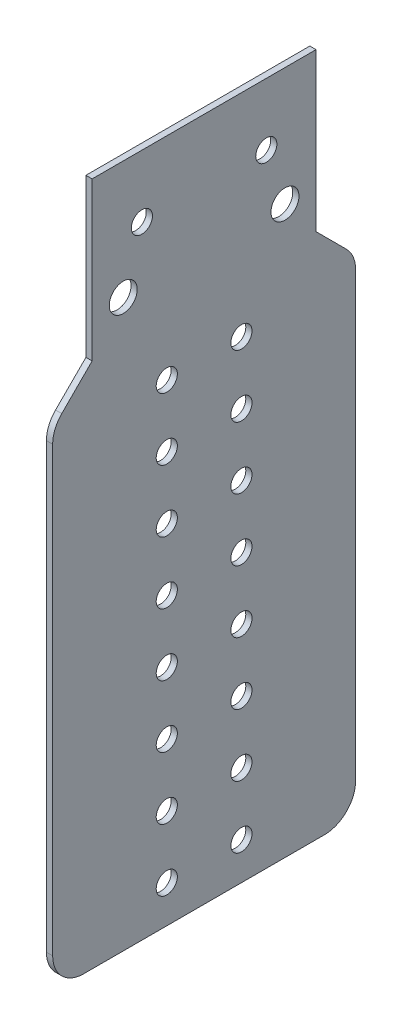
SolidWorks part; units mm, degrees
material "PVC 0.007 Plasticized"
ref_plane "Front Plane" through (0, 0, 0) normal (0, 0, 1) x (1, 0, 0)
ref_plane "Top Plane" through (0, 0, 0) normal (0, 1, 0) x (1, 0, 0)
ref_plane "Right Plane" through (0, 0, 0) normal (1, 0, 0) x (0, 0, -1)
sketch "Sketch1" plane through (0, 0, 0) normal (1, 0, 0) x (0, 0, -1)
  line L1 (-18, 0) -> (18, 0)
  line L2 (-18, 0) -> (-18, -110)
  line L3 (-18, -110) -> (18, -110)
  line L4 (18, 0) -> (18, -110)
  line L5 (-18, 0) -> (18, -110) construction
  line L6 (-18, -110) -> (18, 0) construction
  point P4 (0, -55)
  point P5 (0, 0)
  dimension "D1" = 110
  dimension "D2" = 36
extrude "Boss-Extrude1" add sketch "Sketch1" along normal blind 1 contours L2 L3 L4 L1
hole_wizard "M3 Clearance Hole1" positions "Sketch2" profile "Sketch3" hole size "M3" standard "ISO" end condition through all
sketch "Sketch2" plane through (0, 0, 0) normal (-1, 0, 0) x (0, 0, 1)
  point P0 (-10, -10)
  point P3 (10, -10)
sketch "Sketch3" plane through (0, -10, -10) normal (0, 1, 0) x (0, 0, 1)
  line L0 (0, 0) -> (0, 1)
  line L1 (0, 1) -> (1.7, 1)
  line L2 (1.7, 1) -> (1.7, 0)
  line L5 (1.7, 0) -> (0, 0)
  line L11 (0, -6.35) -> (0, 107.95) construction
  dimension "Thru Hole Dia." = 3.4
  dimension "Thru Hole Depth" = 1
hole_wizard "M4 Clearance Hole1" positions "Sketch4" profile "Sketch5" hole size "M4" standard "ISO" end condition through all
sketch "Sketch4" plane through (0, 0, 0) normal (-1, 0, 0) x (0, 0, 1)
  point P0 (-13, -19)
  point P3 (13, -19)
sketch "Sketch5" plane through (0, -19, -13) normal (0, 1, 0) x (0, 0, 1)
  line L0 (0, 0) -> (0, 1)
  line L1 (0, 1) -> (2.25, 1)
  line L2 (2.25, 1) -> (2.25, 0)
  line L5 (2.25, 0) -> (0, 0)
  line L11 (0, -6.35) -> (0, 107.95) construction
  dimension "Thru Hole Dia." = 4.5
  dimension "Thru Hole Depth" = 1
sketch "Sketch6" plane through (1, 0, 0) normal (1, 0, 0) x (0, 0, -1)
  line L0 (-18, -110) -> (18, -110) construction
  point P0 (-6, -104)
  point P1 (6, -104)
  dimension "D1" = 12
  dimension "D2" = 6
  dimension "D3" = 6
hole_wizard "M3 Clearance Hole2" positions "Sketch7" profile "Sketch8" hole size "M3" standard "ISO" end condition through all
sketch "Sketch7" plane through (1, 0, 0) normal (1, 0, 0) x (0, 0, -1)
  point P0 (6, -104)
  point P3 (-6, -104)
  point P16 (6, -94)
  point P17 (-6, -94)
  point P18 (6, -84)
  point P19 (-6, -84)
  point P20 (6, -74)
  point P21 (-6, -74)
  point P22 (6, -64)
  point P23 (-6, -64)
  point P24 (6, -54)
  point P25 (-6, -54)
  point P26 (6, -44)
  point P27 (-6, -44)
  point P28 (6, -34)
  point P29 (-6, -34)
  dimension "D1" = 8
sketch "Sketch8" plane through (1, -104, -6) normal (0, 1, 0) x (0, 0, -1)
  line L0 (0, 0) -> (0, 1)
  line L1 (0, 1) -> (1.7, 1)
  line L2 (1.7, 1) -> (1.7, 0)
  line L5 (1.7, 0) -> (0, 0)
  line L11 (0, -6.35) -> (0, 107.95) construction
  dimension "Thru Hole Dia." = 3.4
  dimension "Thru Hole Depth" = 1
sketch "Sketch9" plane through (0, 0, 0) normal (-1, 0, 0) x (0, 0, 1)
  line L0 (18, -25.35) -> (22.8855, -30.2355)
  line L1 (18, 0) -> (18, -110) construction
  line L2 (24.35, -33.7711) -> (24.35, -105)
  line L3 (19.35, -110) -> (18, -110)
  line L4 (18, -110) -> (18, -25.35)
  line L5 (-18, -25.35) -> (-22.8855, -30.2355)
  line L6 (-18, 0) -> (-18, -110) construction
  line L7 (-24.35, -33.7711) -> (-24.35, -105)
  line L8 (-19.35, -110) -> (-18, -110)
  line L9 (-18, -110) -> (-18, -25.35)
  circle A0 centre (13, -19) radius 2.25 construction
  circle A2 centre (-13, -19) radius 2.25 construction
  arc A3 (24.35, -105) -> (19.35, -110) centre (19.35, -105) cw
  arc A4 (-24.35, -105) -> (-19.35, -110) centre (-19.35, -105) ccw
  arc A5 (22.8855, -30.2355) -> (24.35, -33.7711) centre (19.35, -33.7711) cw
  arc A6 (-22.8855, -30.2355) -> (-24.35, -33.7711) centre (-19.35, -33.7711) ccw
  point P18 (-13.8926, -21.0654)
  dimension "D2" = 6.35
  dimension "D5" = 6.35
  dimension "D7" = 5
  dimension "D1" = 6.35
  dimension "D3" = 45
  dimension "D4" = 6.35
  dimension "D6" = 45
extrude "Boss-Extrude2" add sketch "Sketch9" against normal up to surface (1 mm away) up to face at (1, -104, -7.7)
